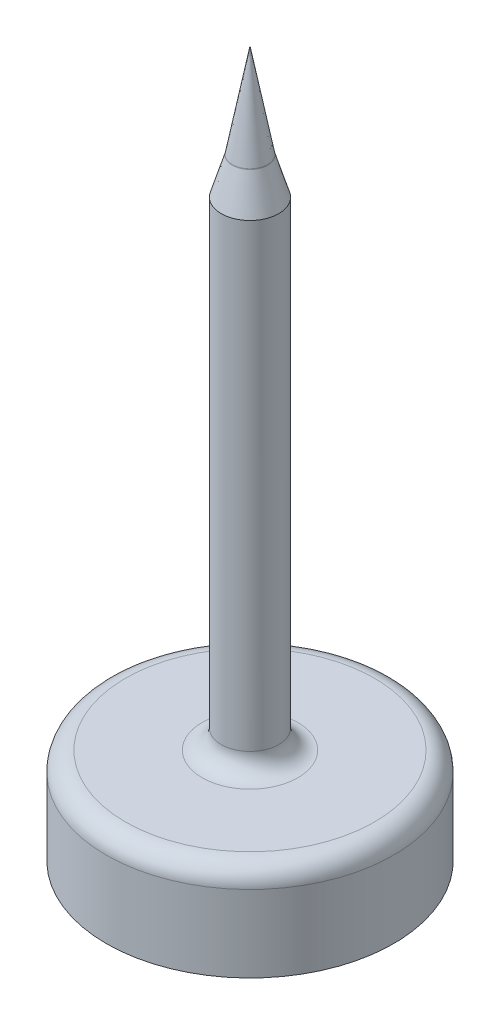
SolidWorks part; units mm, degrees
ref_plane "Plan de face" through (0, 0, 0) normal (0, 0, 1) x (1, 0, 0)
ref_plane "Plan de dessus" through (0, 0, 0) normal (0, 1, 0) x (1, 0, 0)
ref_plane "Plan de droite" through (0, 0, 0) normal (1, 0, 0) x (0, 0, -1)
sketch "Esquisse1" plane through (0, 0, 0) normal (1, 0, 0) x (0, 0, -1)
  line L0 (0, 0) -> (0, 84.1333) construction
  line L1 (0, 0) -> (15, 0)
  line L2 (15, 0) -> (15, 10)
  line L3 (15, 10) -> (3, 10)
  line L4 (3, 10) -> (3, 60)
  line L5 (3, 60) -> (1.8468, 63.8302)
  line L6 (1.8468, 63.8302) -> (0, 73.6582)
  line L7 (0, 0) -> (0, 73.6582)
  point P3 (7.36, 10)
  point P10 (0, 0)
  point P11 (0, 0)
  point P12 (2.8009, 49.6113)
  point P13 (0, 57.2522)
  point P14 (2.8009, 43.0243)
  point P15 (0, 76.2245)
  point P16 (0, 0)
  point P17 (1.4282, 65.2208)
  dimension "D1" = 10
  dimension "D2" = 15
  dimension "D3" = 6
  dimension "D4" = 50
  dimension "D5" = 4
  dimension "D6" = 10
revolve "Révolution1" add sketch "Esquisse1" angle 360 about L0
fillet "Congé1" radius 2 1 edges at (0, 10, -15)
fillet "Congé2" radius 2 1 edges at (0, 10, -3)
fillet "Congé3" radius 0.5 1 edges at (0, 63.8302, -1.8468)
